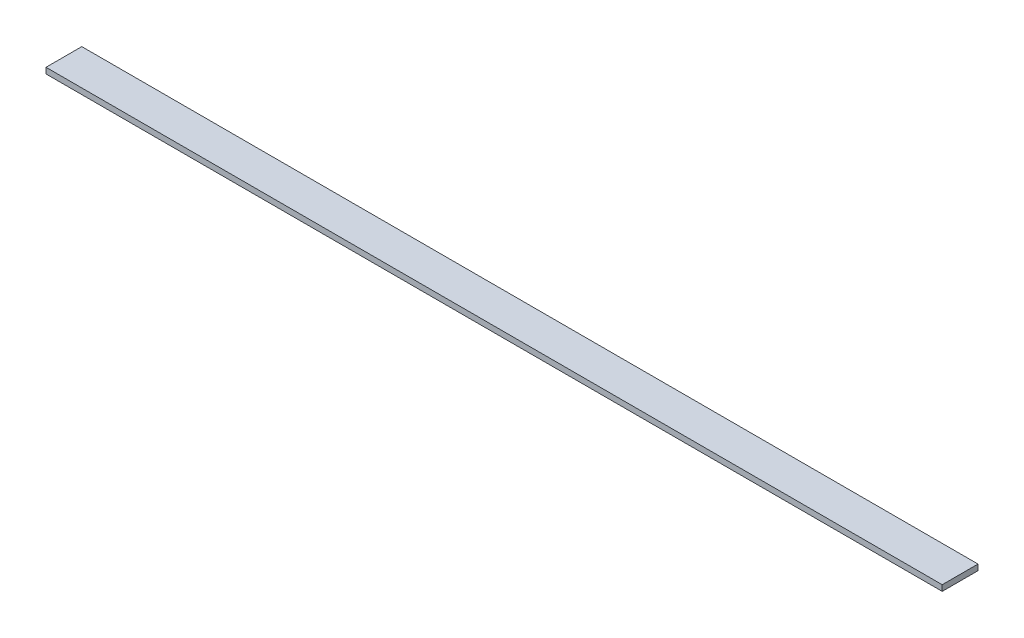
SolidWorks part; units mm, degrees
material "Pine"
ref_plane "Front Plane" through (0, 0, 0) normal (0, 0, 1) x (1, 0, 0)
ref_plane "Top Plane" through (0, 0, 0) normal (0, 1, 0) x (1, 0, 0)
ref_plane "Right Plane" through (0, 0, 0) normal (1, 0, 0) x (0, 0, -1)
sketch "Sketch3" plane through (0, 0, 0) normal (0, 1, 0) x (1, 0, 0)
  line L1 (-3811.4111, 1664.2292) -> (2071.8639, 1664.2292)
  line L2 (-3811.4111, 1664.2292) -> (-3811.4111, 1429.2792)
  line L3 (-3811.4111, 1429.2792) -> (2071.8639, 1429.2792)
  line L4 (2071.8639, 1664.2292) -> (2071.8639, 1429.2792)
  dimension "D1" = 234.95
  dimension "D2" = 5883.275
extrude "Boss-Extrude1" add sketch "Sketch3" along normal blind 38.1
